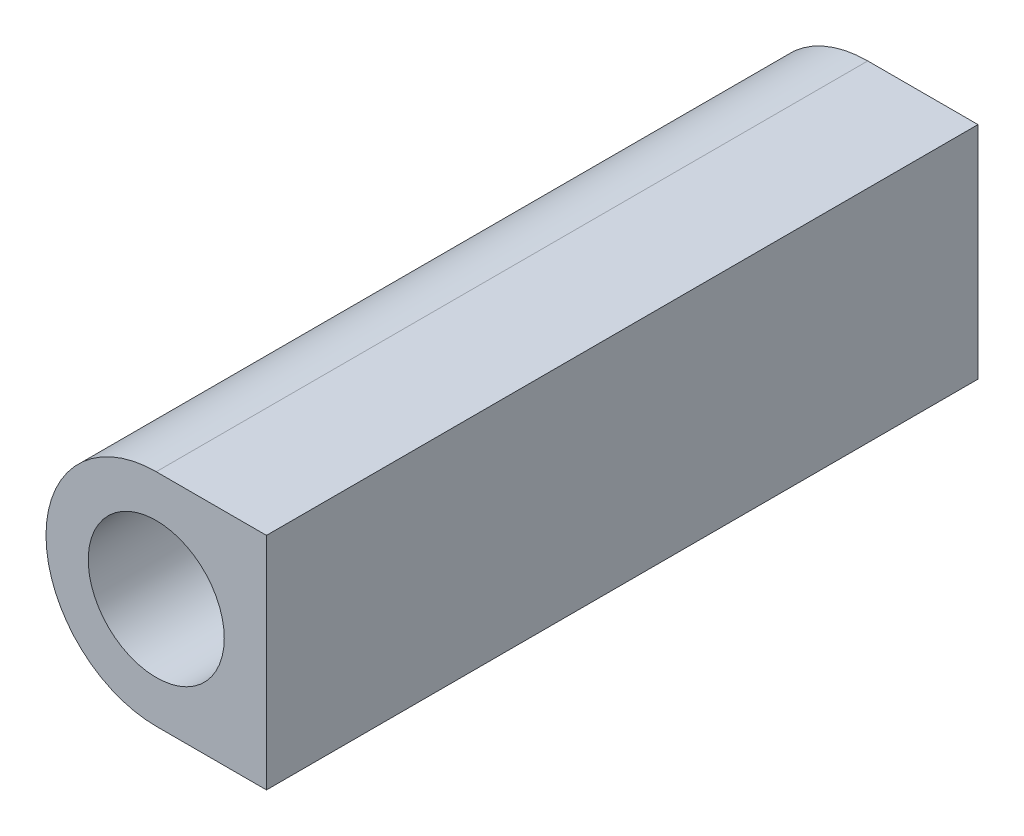
SolidWorks part; units mm, degrees
ref_plane "Front Plane" through (0, 0, 0) normal (1, 0, 0) x (0, 1, 0)
ref_plane "Top Plane" through (0, 0, 0) normal (0, 0, 1) x (0, 1, 0)
ref_plane "Right Plane" through (0, 0, 0) normal (0, 1, 0) x (-1, 0, 0)
sketch "Sketch3" plane through (0, 0, 0) normal (0, 0, 1) x (0, 1, 0)
  line L0 (-12.5, 0) -> (-12.5, -12.5)
  line L1 (-12.5, -12.5) -> (12.5, -12.5)
  line L2 (12.5, -12.5) -> (12.5, 0)
  arc A1 (12.5, 0) -> (-12.5, 0) centre (0, 0) ccw
  dimension "D1" = 25
  dimension "D2" = 12.5
  dimension "D3" = 12.5
extrude "Boss-Extrude5" add sketch "Sketch3" along normal blind 80.6824 contours A1 L0 L1 L2
sketch "Sketch6" plane through (0, 0, 80.6824) normal (0, 0, 1) x (1, 0, 0)
  circle A0 centre (0, 0) radius 7.7131
extrude "Cut-Extrude3" cut sketch "Sketch6" against normal blind 25
sketch "Sketch7" plane through (0, 0, 0) normal (0, 0, -1) x (1, 0, 0)
  circle A0 centre (0, 0) radius 3.5
  dimension "D1" = 7
extrude "Cut-Extrude4" cut sketch "Sketch7" against normal blind 5 contours A0
sketch "Sketch8" plane through (0, 0, 55.6824) normal (0, 0, 1) x (1, 0, 0)
  circle A0 centre (0, 0) radius 7.7131
extrude "Cut-Extrude5" cut sketch "Sketch8" against normal blind 50
sketch "Sketch9" plane through (0, 0, 0) normal (0, 0, -1) x (1, 0, 0)
  circle A0 centre (0, 0) radius 3.5
extrude "Cut-Extrude6" cut sketch "Sketch9" against normal blind 50
